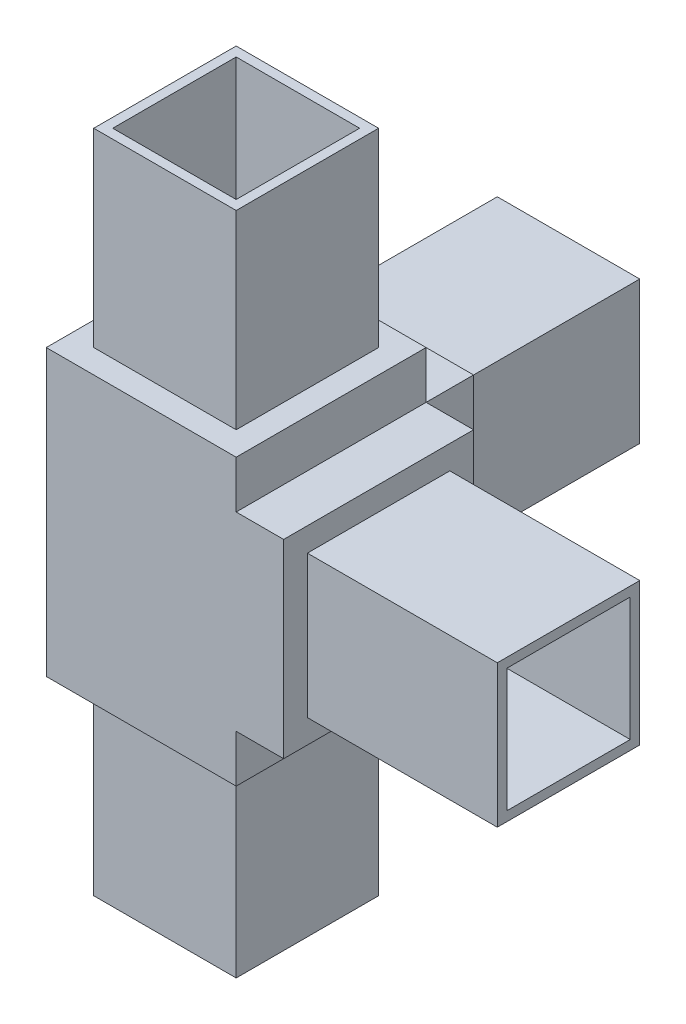
SolidWorks part; units mm, degrees
ref_plane "Alzado" through (0, 0, 0) normal (0, 0, 1) x (1, 0, 0)
ref_plane "Planta" through (0, 0, 0) normal (0, 1, 0) x (1, 0, 0)
ref_plane "Vista lateral" through (0, 0, 0) normal (1, 0, 0) x (0, 0, -1)
sketch "Croquis1" plane through (0, 0, 0) normal (0, 1, 0) x (1, 0, 0)
  line L1 (20, -20) -> (-20, -20)
  line L2 (20, -20) -> (20, 20)
  line L3 (20, 20) -> (-20, 20)
  line L4 (-20, -20) -> (-20, 20)
  line L5 (20, -20) -> (-20, 20) construction
  line L6 (20, 20) -> (-20, -20) construction
  line L7 (20, -20) -> (70, -20)
  line L8 (20, -20) -> (20, 20)
  line L9 (20, 20) -> (70, 20)
  line L10 (70, -20) -> (70, 20)
  line L11 (-20, 20) -> (20, 20)
  line L12 (-20, 20) -> (-20, 70)
  line L13 (-20, 70) -> (20, 70)
  line L14 (20, 20) -> (20, 70)
  point P0 (0, 0)
  dimension "D1" = 40
  dimension "D2" = 40
  dimension "D3" = 50
  dimension "D4" = 50
extrude "Extruir1" add sketch "Croquis1" along normal blind 40 contours L3 L14 L13 L12 | L4 L1 L2 L3 | L7 L10 L9 L2
sketch "Croquis5" plane through (0, 0, 0) normal (0, -1, 0) x (1, 0, 0)
  line L1 (-20, 20) -> (20, 20)
  line L2 (-20, 20) -> (-20, -20)
  line L3 (-20, -20) -> (20, -20)
  line L4 (20, 20) -> (20, -20)
extrude "Extruir4" add sketch "Croquis5" along normal blind 50
sketch "Croquis8" plane through (0, 40, 0) normal (0, 1, 0) x (1, 0, 0)
  line L1 (-20, -20) -> (20, -20)
  line L2 (-20, -20) -> (-20, 20)
  line L3 (-20, 20) -> (20, 20)
  line L4 (20, -20) -> (20, 20)
extrude "Extruir6" add sketch "Croquis8" along normal blind 50
sketch "Croquis9" plane through (0, 90, 0) normal (0, 1, 0) x (1, 0, 0)
  line L0 (-15, 15) -> (-15, -15)
  line L1 (-15, -15) -> (15, -15)
  line L2 (15, -15) -> (15, 15)
  line L3 (15, 15) -> (-15, 15)
  line L4 (-20, 20) -> (-20, -20)
  line L5 (-20, -20) -> (20, -20)
  line L6 (20, -20) -> (20, 20)
  line L7 (20, 20) -> (-20, 20)
  line L8 (-20, 20) -> (-20, -20)
  line L9 (-20, -20) -> (20, -20)
  line L10 (20, -20) -> (20, 20)
  line L11 (20, 20) -> (-20, 20)
  dimension "D1" = 0
  dimension "D2" = 5
extrude "Extruir7" cut sketch "Croquis9" against normal blind 40
sketch "Croquis2" plane through (70, 0, 0) normal (1, 0, 0) x (0, 0, -1)
  line L4 (-20, 0) -> (20, 0)
  line L5 (20, 0) -> (20, 40)
  line L6 (20, 40) -> (-20, 40)
  line L7 (-20, 40) -> (-20, 0)
  line L8 (-20, 0) -> (20, 0)
  line L9 (20, 0) -> (20, 40)
  line L10 (20, 40) -> (-20, 40)
  line L11 (-20, 40) -> (-20, 0)
  line L16 (-15, 5) -> (15, 5)
  line L17 (15, 5) -> (15, 35)
  line L18 (15, 35) -> (-15, 35)
  line L19 (-15, 35) -> (-15, 5)
  line L20 (-15, 5) -> (15, 5)
  line L21 (15, 5) -> (15, 35)
  line L22 (15, 35) -> (-15, 35)
  line L23 (-15, 35) -> (-15, 5)
  dimension "D1" = 0
  dimension "D2" = 5
extrude "Extruir2" cut sketch "Croquis2" against normal blind 40
sketch "Croquis3" plane through (0, 0, -70) normal (0, 0, -1) x (-1, 0, 0)
  line L0 (-15, 5) -> (15, 5)
  line L1 (15, 5) -> (15, 35)
  line L2 (15, 35) -> (-15, 35)
  line L3 (-15, 35) -> (-15, 5)
  line L4 (-20, 0) -> (20, 0)
  line L5 (20, 0) -> (20, 40)
  line L6 (20, 40) -> (-20, 40)
  line L7 (-20, 40) -> (-20, 0)
  line L8 (-20, 0) -> (20, 0)
  line L9 (20, 0) -> (20, 40)
  line L10 (20, 40) -> (-20, 40)
  line L11 (-20, 40) -> (-20, 0)
  dimension "D1" = 0
  dimension "D2" = 5
extrude "Extruir3" cut sketch "Croquis3" against normal blind 40
sketch "Croquis7" plane through (0, -50, 0) normal (0, -1, 0) x (1, 0, 0)
  line L0 (-15, 15) -> (-15, -15)
  line L1 (-15, -15) -> (15, -15)
  line L2 (15, -15) -> (15, 15)
  line L3 (15, 15) -> (-15, 15)
  line L4 (-20, 20) -> (-20, -20)
  line L5 (-20, -20) -> (20, -20)
  line L6 (20, -20) -> (20, 20)
  line L7 (20, 20) -> (-20, 20)
  line L8 (-20, 20) -> (-20, -20)
  line L9 (-20, -20) -> (20, -20)
  line L10 (20, -20) -> (20, 20)
  line L11 (20, 20) -> (-20, 20)
  dimension "D1" = 0
  dimension "D2" = 5
extrude "Extruir5" cut sketch "Croquis7" against normal blind 40
shell "Vaciado1" thickness 2
